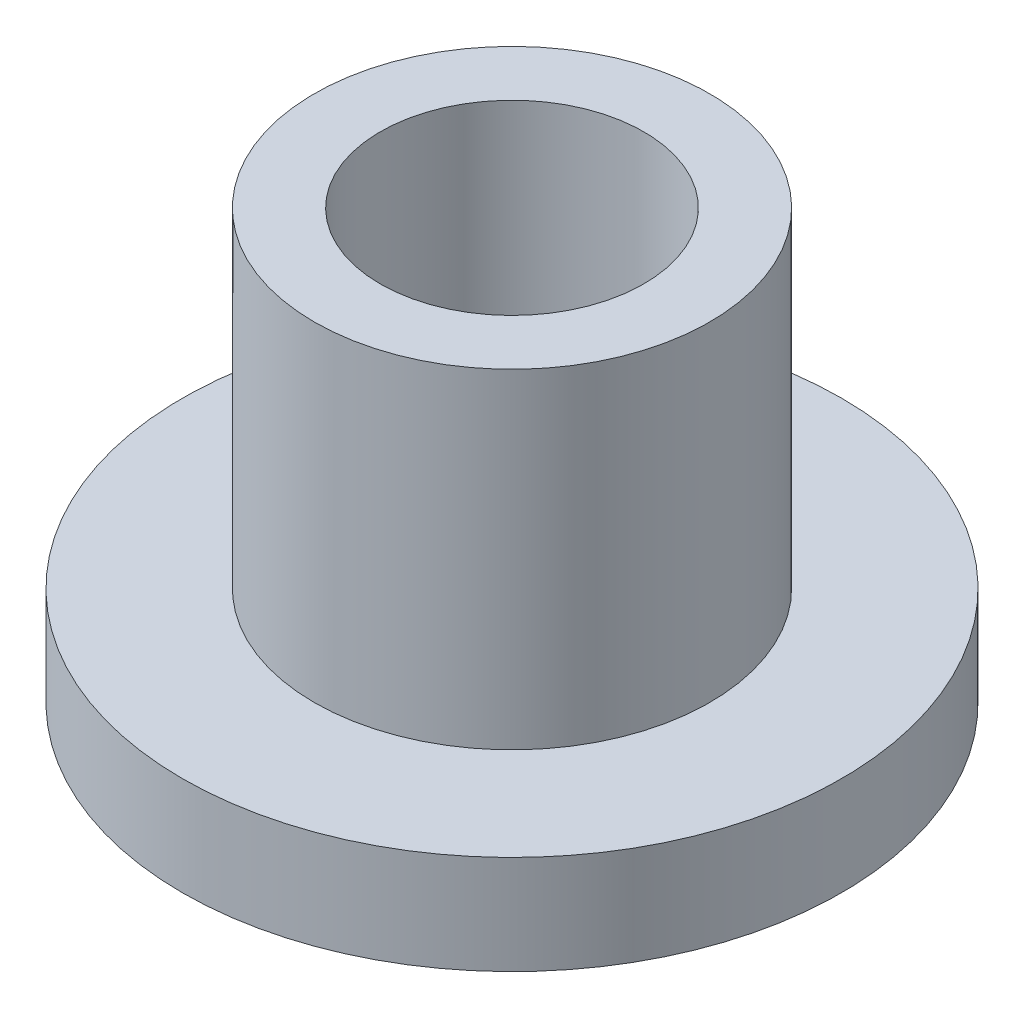
SolidWorks part; units mm, degrees
ref_plane "Спереди" through (0, 0, 0) normal (0, 0, 1) x (1, 0, 0)
ref_plane "Сверху" through (0, 0, 0) normal (0, 1, 0) x (1, 0, 0)
ref_plane "Справа" through (0, 0, 0) normal (1, 0, 0) x (0, 0, -1)
sketch "Эскиз1" plane through (0, 0, 0) normal (0, 1, 0) x (1, 0, 0)
  circle A0 centre (0, 0) radius 20
extrude "Вытянуть1" add sketch "Эскиз1" along normal blind 6
sketch "Эскиз2" plane through (0, 6, 0) normal (0, 1, 0) x (1, 0, 0)
  circle A0 centre (0, 0) radius 12
extrude "Вытянуть2" add sketch "Эскиз2" along normal blind 20
sketch "Эскиз3" plane through (0, 26, 0) normal (0, 1, 0) x (-1, 0, 0)
  circle A0 centre (0, 0) radius 8
extrude "Вытянуть3" cut sketch "Эскиз3" against normal blind 25
sketch "Эскиз4" plane through (0, 0, 0) normal (0, -1, 0) x (1, 0, 0)
  circle A0 centre (0, 0) radius 12
extrude "Вытянуть4" [suppressed] cut sketch "Эскиз4" against normal blind 10
